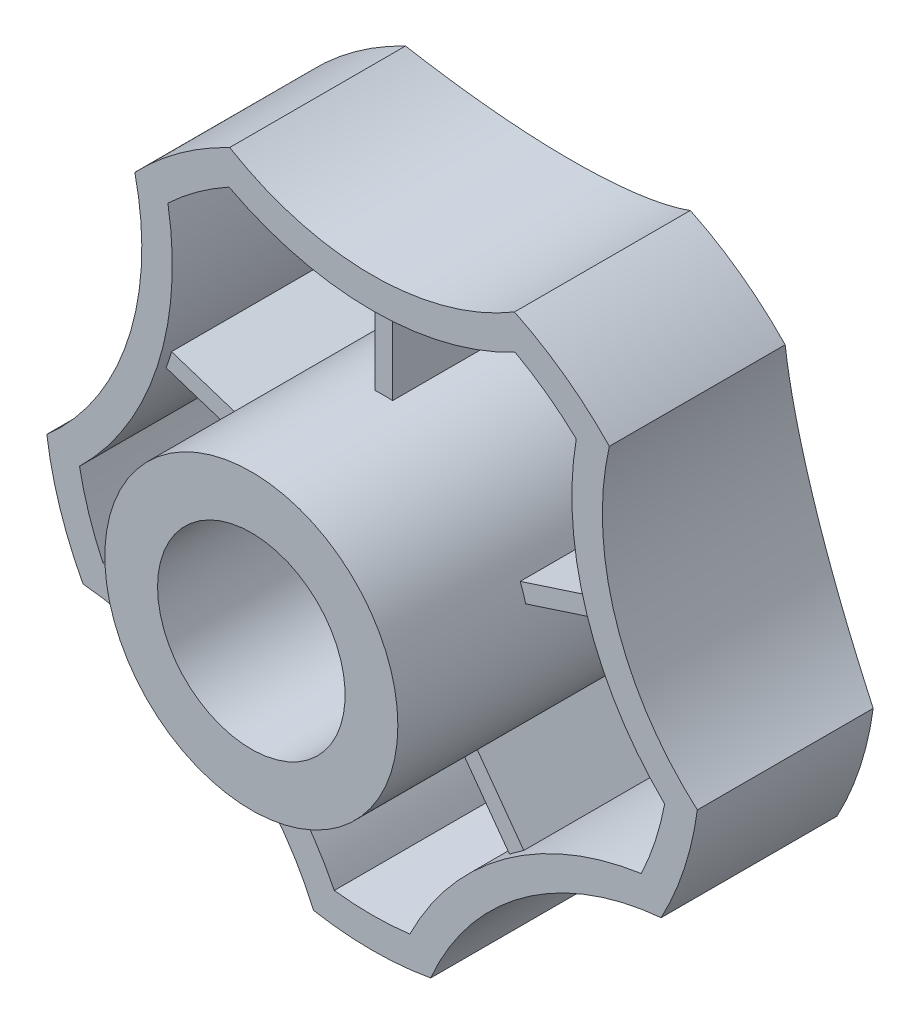
SolidWorks part; units mm, degrees
ref_plane "Plan de face" through (0, 0, 0) normal (0, 0, 1) x (1, 0, 0)
ref_plane "Plan de dessus" through (0, 0, 0) normal (0, 1, 0) x (1, 0, 0)
ref_plane "Plan de droite" through (0, 0, 0) normal (1, 0, 0) x (0, 0, -1)
sketch "Esquisse1" plane through (0, 0, 0) normal (0, 0, 1) x (1, 0, 0)
  line L0 (0, 0) -> (0, 58.3015) construction
  line L1 (0, 0) -> (-42.3089, 58.2332) construction
  line L2 (0, 0) -> (35.9888, 49.5343) construction
  arc A0 (-12.1484, 25.2273) -> (-20.2385, 19.3495) centre (0, 0) ccw
  arc A1 (-12.1484, 25.2273) -> (12.1484, 25.2273) centre (0, 45.5348) ccw
  arc A2 (20.2385, 19.3495) -> (27.7466, -3.7581) centre (43.3061, 14.071) ccw
  arc A3 (24.6565, -13.2687) -> (5, -27.55) centre (26.7647, -36.8384) ccw
  arc A4 (-5, -27.55) -> (-24.6565, -13.2687) centre (-26.7647, -36.8384) ccw
  arc A5 (-27.7466, -3.7581) -> (-20.2385, 19.3495) centre (-43.3061, 14.071) ccw
  arc A6 (-27.7466, -3.7581) -> (-24.6565, -13.2687) centre (0, 0) ccw
  arc A7 (-5, -27.55) -> (5, -27.55) centre (0, 0) ccw
  arc A8 (24.6565, -13.2687) -> (27.7466, -3.7581) centre (0, 0) ccw
  arc A9 (20.2385, 19.3495) -> (12.1484, 25.2273) centre (0, 0) ccw
  dimension "D1" = 56
  dimension "D2" = 72
  dimension "D3" = 36
  dimension "D4" = 5
  dimension "D5" = 5
extrude "Boss.-Extru.1" add sketch "Esquisse1" along normal blind 20
sketch "Esquisse3" plane through (0, 0, 0) normal (1, 0, 0) x (0, 0, -1)
  line L0 (0, 0) -> (-89.6696, 0) construction
  line L1 (-20, -28) -> (0, -28) construction
  line L2 (-5, -28) -> (3.9979, -28)
  line L4 (0, 0) -> (3.9979, 0)
  line L5 (3.9979, 0) -> (3.9979, -28)
  arc A0 (-5, -28) -> (0, 0) centre (-80.9, 0) ccw
  dimension "D1" = 5
revolve "Enlèvement de matière-Révolution3" cut sketch "Esquisse3" angle 360 about L0
shell "Coque1" thickness 2.6
ref_plane "Plan1" through (0, 0, 30.3) normal (0, 0, 1) x (1, 0, 0)
sketch "Esquisse4" plane through (0, 0, 30.3) normal (0, 0, 1) x (1, 0, 0)
  circle A0 centre (0, 0) radius 12.5
  dimension "D1" = 25
extrude "Boss.-Extru.2" add sketch "Esquisse4" against normal up to surface (26.6958 mm away)
sketch "Esquisse5" plane through (0, 0, 0) normal (0, 1, 0) x (1, 0, 0)
  line L0 (-12.5, -30.3) -> (12.5, -30.3) construction
  line L1 (0, -30.3) -> (8, -30.3)
  line L2 (8, -30.3) -> (8, -14.3)
  line L3 (8, -14.3) -> (7, -14.3)
  line L4 (7, -14.3) -> (7, 4.215)
  line L5 (0, 0) -> (0, -38.7042) construction
  line L6 (7, 4.215) -> (0, 4.215)
  line L7 (0, -30.3) -> (0, 4.215)
  dimension "D1" = 8
  dimension "D2" = 16
  dimension "D3" = 7
revolve "Enlèvement de matière-Révolution4" cut sketch "Esquisse5" angle 360 about L5
ref_plane "Plan2" through (0, 0, 19) normal (0, 0, 1) x (1, 0, 0)
sketch "Esquisse6" plane through (0, 0, 19) normal (0, 0, 1) x (1, 0, 0)
  line L0 (0, 19.271) -> (0, 12.5)
rib "Nervure1" sketch "Esquisse6" sketch "Esquisse6" thickness 1.5 extrusion direction normal to sketch draft on no parameters "D1"=1.5
pattern_circular "Répétition circulaire1" count 5 over 360 about axis through (0, 0, 0) along (0, 0, -1) of "Nervure1"
